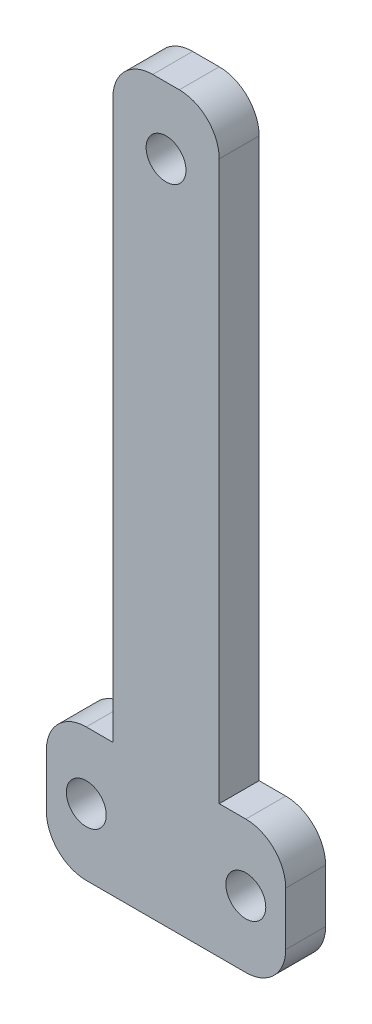
SolidWorks part; units mm, degrees
ref_plane "Alzado" through (0, 0, 0) normal (0, 0, 1) x (1, 0, 0)
ref_plane "Planta" through (0, 0, 0) normal (0, 1, 0) x (1, 0, 0)
ref_plane "Vista lateral" through (0, 0, 0) normal (1, 0, 0) x (0, 0, -1)
sketch "Croquis1" plane through (0, 0, 0) normal (0, 0, 1) x (1, 0, 0)
  line L0 (0, -51.8487) -> (0, 74.7456) construction
  line L1 (-1, -27.5) -> (1, -27.5)
  line L2 (-4, -24.5) -> (-4, 24.5)
  line L3 (-1, 27.5) -> (1, 27.5)
  line L4 (4, -24.5) -> (4, 24.5)
  line L5 (-4, -27.5) -> (4, 27.5) construction
  line L6 (-4, 27.5) -> (4, -27.5) construction
  line L7 (23.9085, 0) -> (-18.7658, 0) construction
  line L8 (2.0098, -22.5) -> (-10.1733, -22.5) construction
  line L9 (-6, -17.5) -> (6, -17.5)
  line L10 (-9, -20.5) -> (-9, -24.5)
  line L11 (-6, -27.5) -> (6, -27.5)
  line L12 (9, -20.5) -> (9, -24.5)
  line L13 (-9, -17.5) -> (9, -27.5) construction
  line L14 (-9, -27.5) -> (9, -17.5) construction
  circle A0 centre (0, 22.5) radius 1.5
  circle A1 centre (0, -22.5) radius 1.5 construction
  arc A2 (1, -27.5) -> (4, -24.5) centre (1, -24.5) ccw
  arc A3 (-1, -27.5) -> (-4, -24.5) centre (-1, -24.5) cw
  arc A4 (1, 27.5) -> (4, 24.5) centre (1, 24.5) cw
  arc A5 (-4, 24.5) -> (-1, 27.5) centre (-1, 24.5) cw
  arc A6 (6, -27.5) -> (9, -24.5) centre (6, -24.5) ccw
  arc A7 (6, -17.5) -> (9, -20.5) centre (6, -20.5) cw
  arc A8 (-9, -24.5) -> (-6, -27.5) centre (-6, -24.5) ccw
  arc A9 (-6, -17.5) -> (-9, -20.5) centre (-6, -20.5) ccw
  circle A10 centre (-6, -22.5) radius 1.5
  circle A11 centre (6, -22.5) radius 1.5
  point P0 (0, 0)
  dimension "D3" = 3
  dimension "D5" = 3
  dimension "D8" = 3
  dimension "D9" = 3
  dimension "D1" = 8
  dimension "D2" = 55
  dimension "D4" = 5
  dimension "D6" = 10
  dimension "D7" = 18
  dimension "D10" = 6
extrude "Saliente-Extruir1" add sketch "Croquis1" along normal mid plane 3 contours A5 L2 L9 L4 A4 L3 A0 | L9 A9 L10 A8 L11 A3 L2 A10 | A3 L1 A2 L4 L9 L2 | A7 L9 L4 A2 L11 A6 L12 A11
